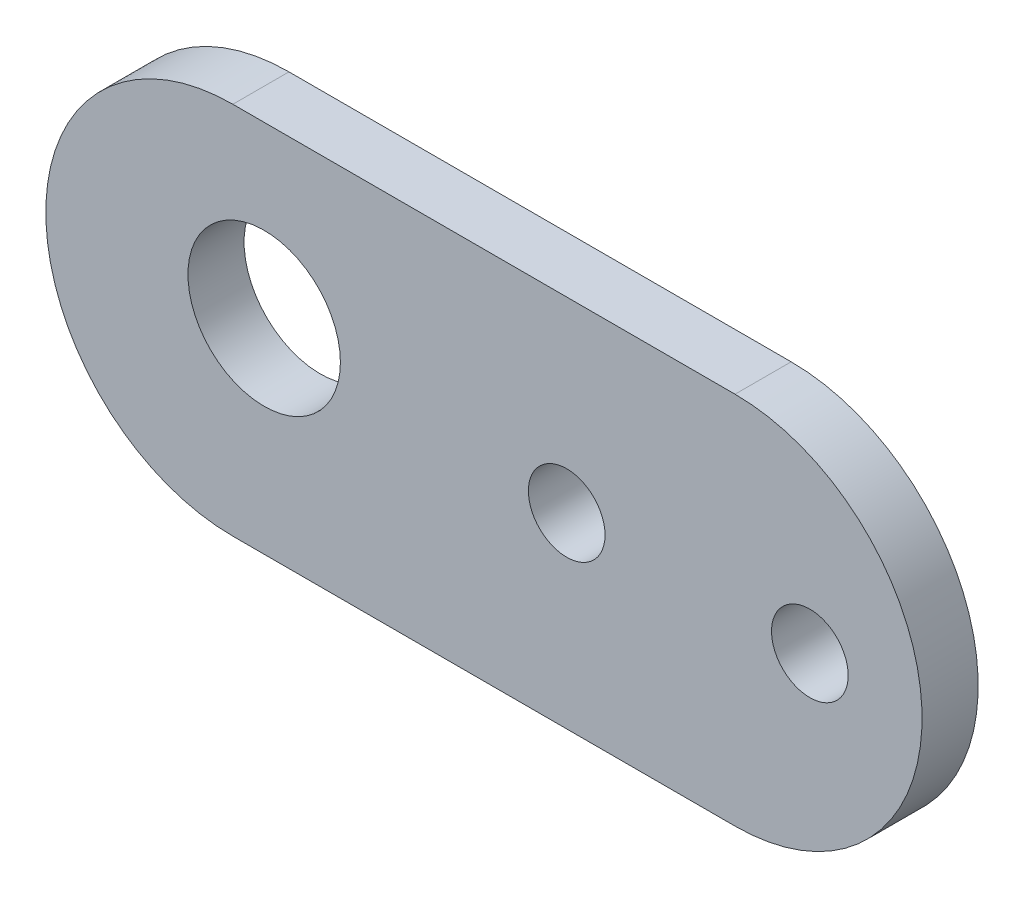
SolidWorks part; units mm, degrees
ref_plane "Front Plane" through (0, 0, 0) normal (0, 0, 1) x (1, 0, 0)
ref_plane "Top Plane" through (0, 0, 0) normal (0, 1, 0) x (1, 0, 0)
ref_plane "Right Plane" through (0, 0, 0) normal (1, 0, 0) x (0, 0, -1)
sketch "Sketch2" plane through (0, 0, 0) normal (0, 0, 1) x (1, 0, 0)
  line L0 (-13.425, 0) -> (13.425, 0) construction
  line L1 (-13.425, 10) -> (13.425, 10)
  line L2 (-13.425, -10) -> (13.425, -10)
  arc A0 (-13.425, 10) -> (-13.425, -10) centre (-13.425, 0) ccw
  arc A1 (13.425, -10) -> (13.425, 10) centre (13.425, 0) ccw
  point P2 (0, 0)
  dimension "D2" = 46.85
  dimension "D1" = 20
extrude "Boss-Extrude1" add sketch "Sketch2" along normal mid plane 3
sketch "Sketch3" plane through (0, 0, 1.5) normal (0, 0, 1) x (1, 0, 0)
  line L0 (23.425, 0) -> (17.425, 0) construction
  line L1 (17.425, 0) -> (4.425, 0) construction
  arc A0 (13.425, -10) -> (13.425, 10) centre (13.425, 0) ccw construction
  circle A1 centre (4.425, 0) radius 2.05
  circle A2 centre (17.425, 0) radius 2.05
  dimension "D1" = 4.1
  dimension "D2" = 6
  dimension "D3" = 13
extrude "Cut-Extrude1" cut sketch "Sketch3" against normal through all
sketch "Sketch4" plane through (0, 0, 1.5) normal (0, 0, 1) x (1, 0, 0)
  line L2 (13.425, 10) -> (-13.425, 10) construction
  circle A0 centre (-11.75, 0.925) radius 4.075
  arc A3 (-13.425, 10) -> (-13.425, -10) centre (-13.425, 0) ccw construction
  dimension "D1" = 8.15
  dimension "D2" = 5
  dimension "D3" = 7.6
extrude "Cut-Extrude2" cut sketch "Sketch4" against normal blind 3
